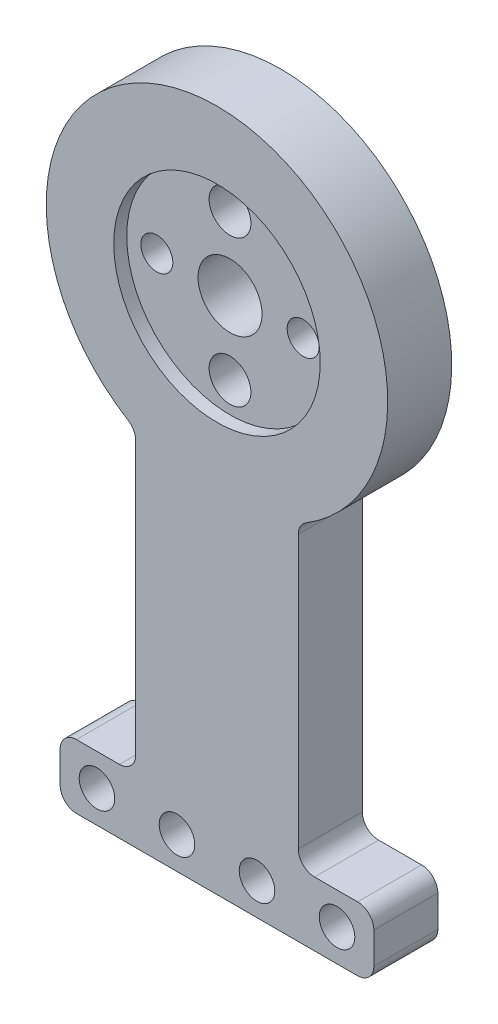
SolidWorks part; units mm, degrees
material "6061-T6 (SS)"
ref_plane "Front Plane" through (0, 0, 0) normal (0, 0, 1) x (1, 0, 0)
ref_plane "Top Plane" through (0, 0, 0) normal (0, 1, 0) x (1, 0, 0)
ref_plane "Right Plane" through (0, 0, 0) normal (1, 0, 0) x (0, 0, -1)
sketch "Sketch1" plane through (0, 0, 0) normal (0, 0, 1) x (1, 0, 0)
  line L0 (0, -26.67) -> (0, -80.01) construction
  line L11 (-12.7, -80.01) -> (12.7, -80.01)
  line L16 (0.8908, 4.9175) -> (-4.7541, -26.2428) construction
  line L17 (4.7541, -26.2428) -> (-0.8908, 4.9175) construction
  line L18 (-12.7, -80.01) -> (-12.7, -23.4521)
  line L19 (12.7, -80.01) -> (12.7, -23.4521)
  circle A9 centre (0, 0) radius 4.9975
  arc A13 (12.7, -23.4521) -> (-12.7, -23.4521) centre (0, 0) ccw
  point P10 (0, -80.01)
  point P20 (0, 0)
  dimension "D1" = 53.34
  dimension "D2" = 25.4
  dimension "D7" = 9.995
  dimension "D3" = 26.67
extrude "Boss-Extrude1" add sketch "Sketch1" along normal mid plane 10
ref_plane "Plane1" through (0, 0, 5) normal (0, 0, 1) x (1, 0, 0)
sketch "Sketch5" plane through (0, 0, 5) normal (0, 0, 1) x (1, 0, 0)
  circle A0 centre (0, 0) radius 16.129
  dimension "D1" = 32.258
extrude "Cut-Extrude2" cut sketch "Sketch5" against normal blind 2.032
sketch "Sketch8" plane through (0, 0, -5) normal (0, 0, 1) x (1, 0, 0)
  circle A0 centre (0, 0) radius 10.25
  dimension "D1" = 20.5
sketch "Sketch19" plane through (0, 0, -5) normal (0, 0, 1) x (1, 0, 0)
  circle A0 centre (0, 0) radius 11.43
  circle A1 centre (-11.43, 0) radius 1.5002
  circle A2 centre (0, 11.43) radius 1.5002
  circle A3 centre (11.43, 0) radius 1.5002
  circle A4 centre (0, -11.43) radius 1.5002
  point P14 (0, 0)
  dimension "D1" = 4
  dimension "D2" = 22.86
hole_wizard "Ø5.0mm Dowel Hole1" positions "3DSketch4" profile "Sketch24" hole size "Ø5.0" standard "ANSI Metric"
sketch3d "3DSketch4"
  point P0 (11.43, 0, -5)
  point P3 (-11.43, 0, -5)
sketch "Sketch24" plane through (11.43, 0, -5) normal (1, 0, 0) x (0, 1, 0)
  line L0 (0, 0) -> (0, 18.0122)
  line L1 (0, 18.0122) -> (2.5, 16.51)
  line L2 (2.5, 16.51) -> (2.5, 0)
  line L5 (2.5, 0) -> (0, 0)
  line L10 (0, 18.0122) -> (-2.5, 16.51) construction
  line L11 (0, -6.35) -> (0, 107.95) construction
  dimension "Hole Dia." = 5
  dimension "Hole Depth" = 16.51
  dimension "Drill Angle" = 118
sketch "Sketch25" plane through (0, 0, -5) normal (0, 0, -1) x (-1, 0, 0)
  circle A0 centre (0, 0) radius 7.8
  dimension "D1" = 15.6
extrude "Cut-Extrude4" [suppressed] cut sketch "Sketch25" against normal blind 1.5
sketch "Sketch26" plane through (0, 0, 0) normal (1, 0, 0) x (0, 0, -1)
  line L0 (-5, 29.337) -> (-5, -29.337) construction
  line L1 (5, -80.01) -> (-5, -80.01)
  line L2 (5, -80.01) -> (5, -70.01)
  line L3 (5, -70.01) -> (-5, -70.01)
  line L4 (-5, -80.01) -> (-5, -70.01)
  dimension "D1" = 10
hole_wizard "CSK for 1/4 Flat Head Machine Screw (100)1" positions "3DSketch5" profile "Sketch27" countersink size "1/4" standard "ANSI Inch"
sketch3d "3DSketch5"
  point P0 (0, 11.43, -5)
  point P3 (0, -11.43, -5)
sketch "Sketch27" plane through (0, 11.43, -5) normal (1, 0, 0) x (0, 1, 0)
  line L0 (0, 0) -> (0, 18.4711)
  line L1 (0, 18.4711) -> (3.2639, 16.51)
  line L2 (3.2639, 16.51) -> (3.2639, 2.6641)
  line L3 (3.2639, 2.6641) -> (6.4389, 0)
  line L5 (6.4389, 0) -> (0, 0)
  line L6 (-3.2639, 2.6641) -> (-6.4389, 0) construction
  line L10 (0, 18.4711) -> (-3.2639, 16.51) construction
  line L11 (0, -6.35) -> (0, 107.95) construction
  dimension "Hole Dia." = 6.5278
  dimension "Hole Depth" = 16.51
  dimension "Near C'Sink Dia." = 12.8778
  dimension "Near C'Sink Angle" = 100
  dimension "Drill Angle" = 118
extrude "Boss-Extrude2" add sketch "Sketch26" along normal mid plane 49
fillet "Fillet1" radius 2.54 8 edges at (24.5, -80.01, 0) (24.5, -70.01, 0) (12.7, -70.01, 0) (-12.7, -70.01, 0) (-24.5, -70.01, 0) (-24.5, -80.01, 0) (12.7, -23.4521, 0) (-12.7, -23.4521, 0)
sketch "Sketch28" plane through (0, 0, -5) normal (0, 0, -1) x (-1, 0, 0)
  line L0 (-24.5, -77.47) -> (-24.5, -72.55) construction
  circle A0 centre (-18.75, -75.01) radius 2.6508
  circle A1 centre (-6.25, -75.01) radius 2.6508
  circle A2 centre (6.25, -75.01) radius 2.6508
  circle A3 centre (18.75, -75.01) radius 2.6508
  dimension "D1" = 5.75
  dimension "D3" = 12.5
  dimension "D2" = 4
hole_wizard "7/32 (0.21875) Diameter Hole1" positions "3DSketch6" profile "Sketch29" hole size "7/32" standard "ANSI Inch"
sketch3d "3DSketch6"
  point P0 (-18.75, -75.01, -5)
  point P3 (-6.25, -75.01, -5)
  point P6 (6.25, -75.01, -5)
  point P9 (18.75, -75.01, -5)
sketch "Sketch29" plane through (-18.75, -75.01, -5) normal (1, 0, 0) x (0, 1, 0)
  line L0 (0, 0) -> (0, 18.1793)
  line L1 (0, 18.1793) -> (2.7781, 16.51)
  line L2 (2.7781, 16.51) -> (2.7781, 0)
  line L5 (2.7781, 0) -> (0, 0)
  line L10 (0, 18.1793) -> (-2.7781, 16.51) construction
  line L11 (0, -6.35) -> (0, 107.95) construction
  dimension "Hole Dia." = 5.5562
  dimension "Hole Depth" = 16.51
  dimension "Drill Angle" = 118
